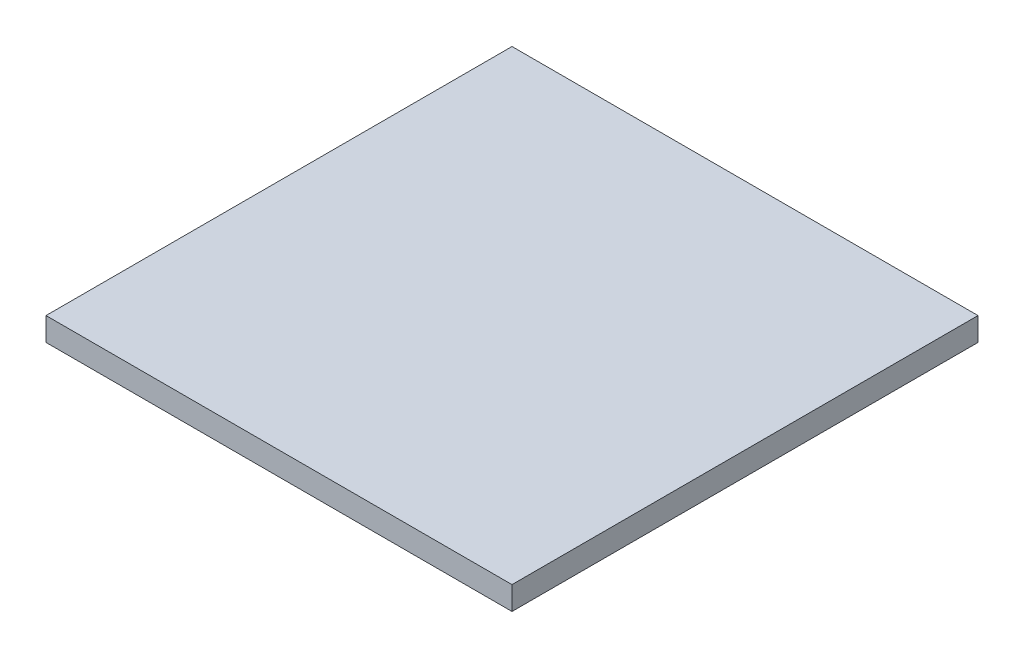
SolidWorks part; units mm, degrees
material "Rubber"
ref_plane "Front Plane" through (0, 0, 0) normal (0, 0, 1) x (1, 0, 0)
ref_plane "Top Plane" through (0, 0, 0) normal (0, 1, 0) x (1, 0, 0)
ref_plane "Right Plane" through (0, 0, 0) normal (1, 0, 0) x (0, 0, -1)
sketch "Sketch1" plane through (0, 0, 0) normal (0, 1, 0) x (1, 0, 0)
  line L1 (0, 0) -> (100, 0)
  line L2 (0, 0) -> (0, 100)
  line L3 (0, 100) -> (100, 100)
  line L4 (100, 0) -> (100, 100)
  dimension "D1" = 100
  dimension "D2" = 100
extrude "Boss-Extrude1" add sketch "Sketch1" along normal blind 5
